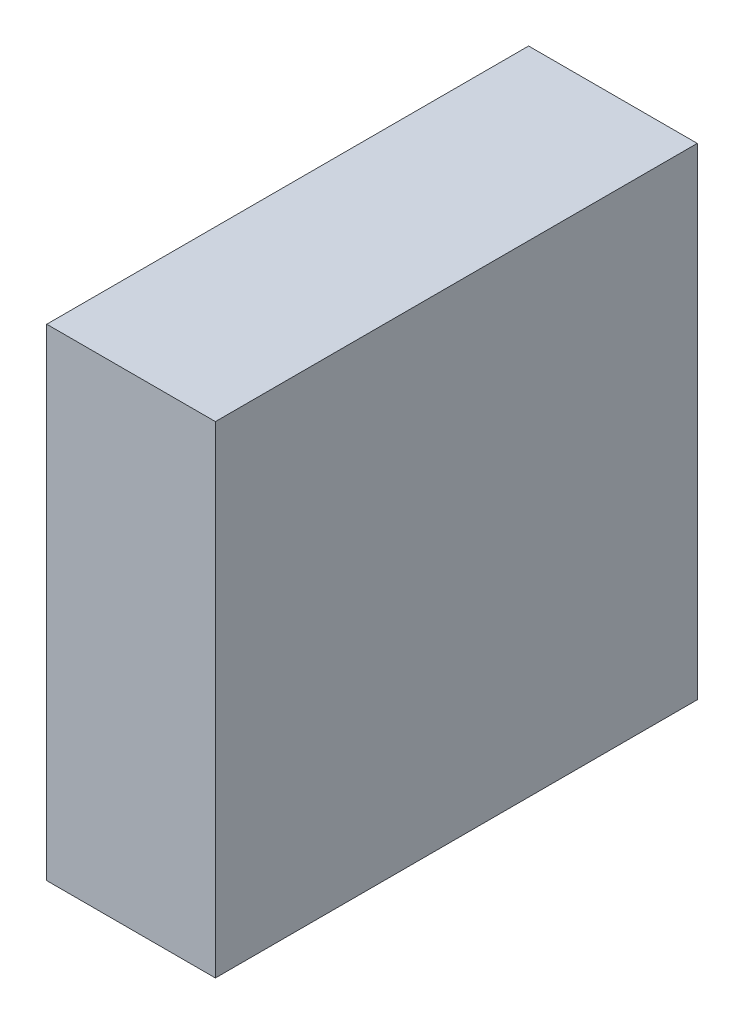
SolidWorks part; units mm, degrees
ref_plane "Front Plane" through (0, 0, 0) normal (0, 0, 1) x (1, 0, 0)
ref_plane "Top Plane" through (0, 0, 0) normal (0, 1, 0) x (1, 0, 0)
ref_plane "Right Plane" through (0, 0, 0) normal (1, 0, 0) x (0, 0, -1)
sketch "Sketch1" plane through (0, 0, 0) normal (1, 0, 0) x (0, 0, -1)
  line L1 (0, 0) -> (254, 0)
  line L2 (0, 0) -> (0, 254)
  line L3 (0, 254) -> (254, 254)
  line L4 (254, 0) -> (254, 254)
  dimension "D1" = 254
  dimension "D2" = 254
extrude "Boss-Extrude1" add sketch "Sketch1" along normal blind 88.9
